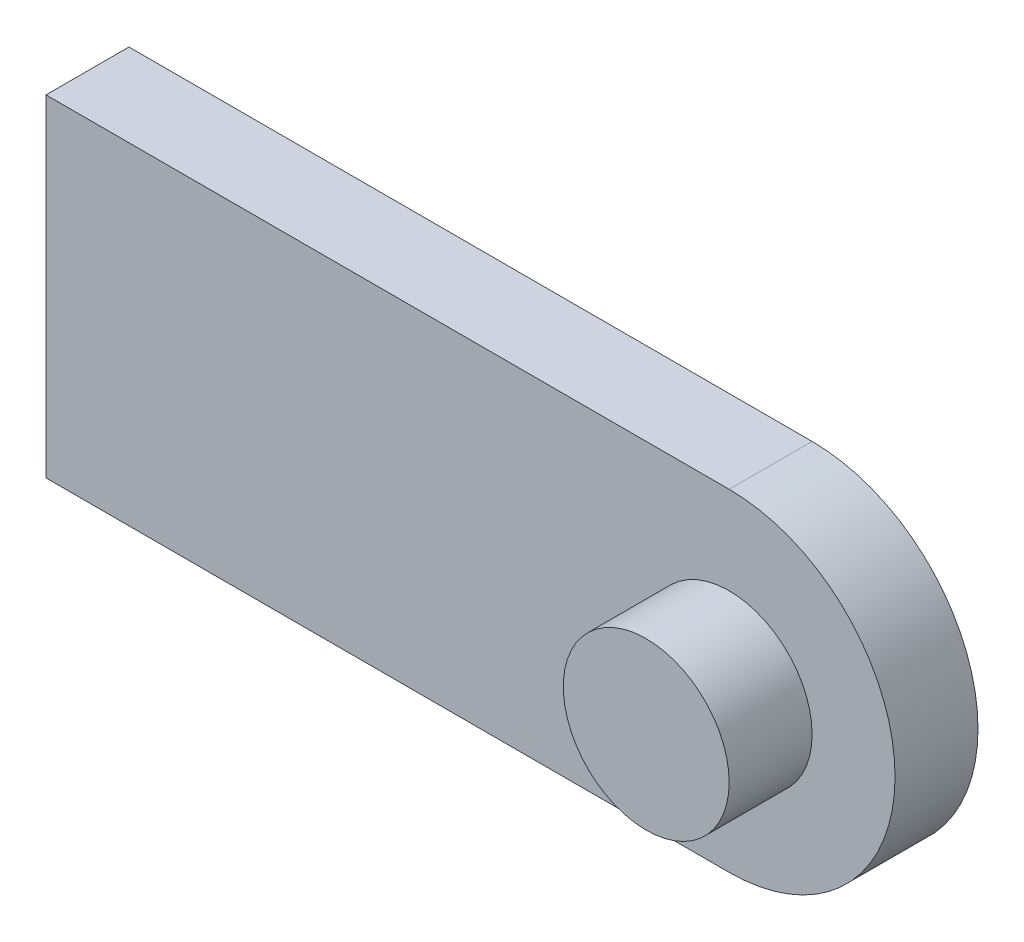
SolidWorks part; units mm, degrees
ref_plane "정면" through (0, 0, 0) normal (0, 0, 1) x (1, 0, 0)
ref_plane "윗면" through (0, 0, 0) normal (0, 1, 0) x (1, 0, 0)
ref_plane "우측면" through (0, 0, 0) normal (1, 0, 0) x (0, 0, -1)
sketch "스케치1" plane through (0, 0, 0) normal (0, 0, 1) x (1, 0, 0)
  line L5 (0, 20) -> (-82.3639, 20)
  line L7 (0, -20) -> (-82.3639, -20)
  line L8 (-82.3639, 20) -> (-82.3639, -20)
  arc A2 (0, -20) -> (0, 20) centre (0, 0) ccw
extrude "보스-돌출1" add sketch "스케치1" along normal blind 10
sketch "스케치2" plane through (0, 0, 10) normal (0, 0, 1) x (1, 0, 0)
  circle A0 centre (0, -0.5932) radius 10
extrude "보스-돌출2" add sketch "스케치2" along normal blind 10
